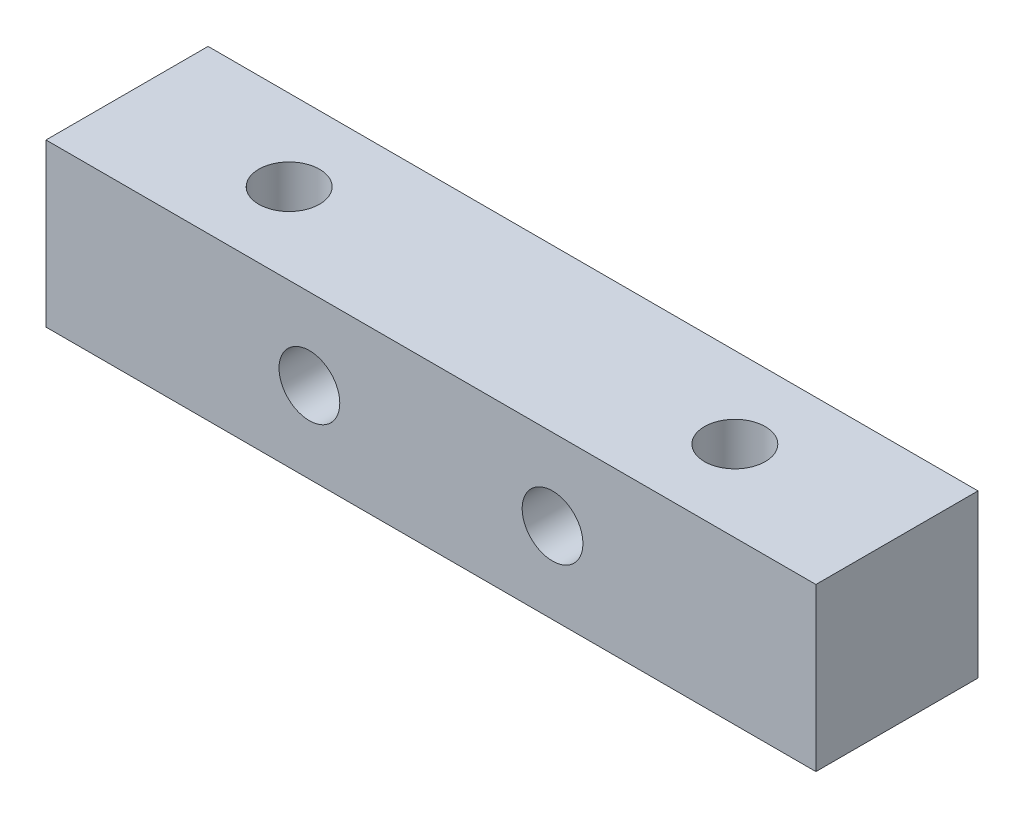
SolidWorks part; units mm, degrees
material "AISI 304"
ref_plane "前视基准面" through (0, 0, 0) normal (0, 0, 1) x (1, 0, 0)
ref_plane "上视基准面" through (0, 0, 0) normal (0, 1, 0) x (1, 0, 0)
ref_plane "右视基准面" through (0, 0, 0) normal (1, 0, 0) x (0, 0, -1)
other "Configuration Table"
sketch "草图1" plane through (0, 0, 0) normal (0, 1, 0) x (1, 0, 0)
  line L1 (-19, -4) -> (19, -4)
  line L2 (-19, -4) -> (-19, 4)
  line L3 (-19, 4) -> (19, 4)
  line L4 (19, -4) -> (19, 4)
  line L5 (-19, -4) -> (19, 4) construction
  line L6 (-19, 4) -> (19, -4) construction
  circle A0 centre (-11, 0) radius 1.5
  circle A1 centre (11, 0) radius 1.5
  point P0 (0, 0)
  dimension "D3" = 3
  dimension "D4" = 3
  dimension "D5" = 22
  dimension "D6" = 8
  dimension "D8" = 4
  dimension "D1" = 38
  dimension "D2" = 8
  dimension "D7" = 4
extrude "凸台-拉伸1" add sketch "草图1" along normal blind 8
sketch "草图2" plane through (0, 0, 4) normal (0, 0, 1) x (1, 0, 0)
  line L0 (0, 0) -> (0, 13.2002) construction
  line L1 (-19, 8) -> (19, 8) construction
  circle A0 centre (-6, 4) radius 1.5
  circle A1 centre (6, 4) radius 1.5
  dimension "D1" = 3
  dimension "D2" = 4
  dimension "D3" = 12
extrude "切除-拉伸1" cut sketch "草图2" against normal blind 8
